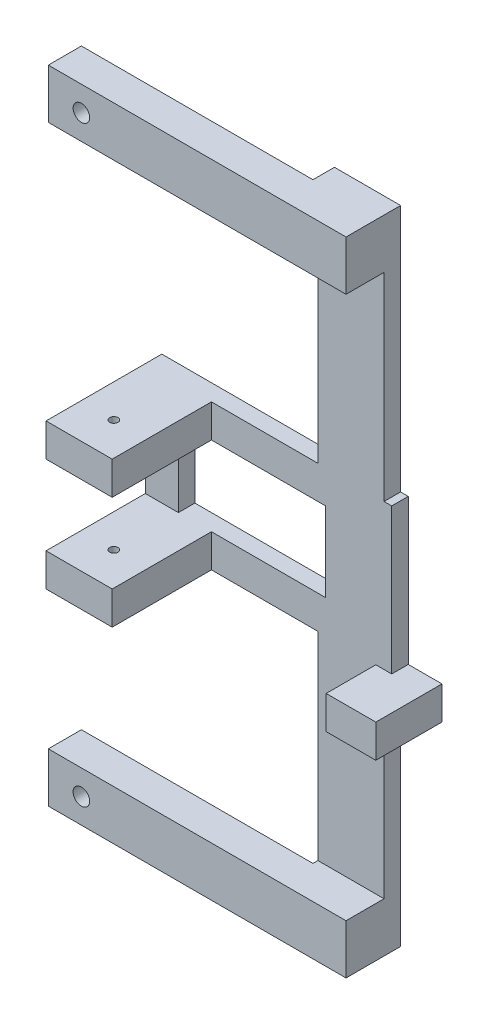
SolidWorks part; units mm, degrees
ref_plane "Front Plane" through (0, 0, 0) normal (0, 0, 1) x (1, 0, 0)
ref_plane "Top Plane" through (0, 0, 0) normal (0, 1, 0) x (1, 0, 0)
ref_plane "Right Plane" through (0, 0, 0) normal (1, 0, 0) x (0, 0, -1)
sketch "Sketch2" plane through (0, 0, 0) normal (0, 0, 1) x (1, 0, 0)
  line L0 (-5.9086, 0.2686) -> (16.6974, 0.2686)
  line L1 (16.6974, 0.2686) -> (16.6974, 12.4606)
  line L2 (16.6974, 12.4606) -> (-5.9086, 12.4606)
  line L3 (-5.9086, 12.4606) -> (-5.9086, 0.2686)
  line L4 (26.8574, 17.5406) -> (26.8574, -4.8114)
  line L6 (-10.9886, -4.8114) -> (-10.9886, 17.5406)
  line L13 (-10.9886, -4.8114) -> (15.521, -4.8114)
  line L16 (26.8574, 17.5406) -> (25.681, 17.5406)
  line L18 (15.521, 17.5406) -> (-10.9886, 17.5406)
  line L19 (15.521, -4.8114) -> (15.521, -42.9114)
  line L20 (15.521, -42.9114) -> (25.681, -42.9114)
  line L21 (25.681, -42.9114) -> (25.681, -4.8114)
  line L22 (25.681, 17.5406) -> (25.681, 55.6406)
  line L23 (25.681, 55.6406) -> (15.521, 55.6406)
  line L24 (15.521, 55.6406) -> (15.521, 17.5406)
  line L25 (25.681, -4.8114) -> (26.8574, -4.8114)
  dimension "D1" = 22.352
  dimension "D2" = 5.08
  dimension "D3" = 10.16
  dimension "D4" = 10.16
  dimension "D5" = 12.192
  dimension "D6" = 22.606
  dimension "D7" = 22.352
  dimension "D8" = 5.08
  dimension "D9" = 38.1
  dimension "D10" = 1.1764
extrude "Boss-Extrude2" add sketch "Sketch2" along normal blind 2.54
sketch "Sketch3" plane through (0, 0, 2.54) normal (0, 0, 1) x (1, 0, 0)
  line L0 (-10.9886, 17.5406) -> (-10.9886, -4.8114) construction
  line L1 (-0.8286, 0.2686) -> (-10.9886, 0.2686)
  line L2 (-0.8286, 0.2686) -> (-0.8286, -4.8114)
  line L3 (-0.8286, -4.8114) -> (-10.9886, -4.8114)
  line L4 (-10.9886, 0.2686) -> (-10.9886, -4.8114)
  line L5 (-10.9886, -4.8114) -> (15.521, -4.8114) construction
  dimension "D1" = 10.16
extrude "Boss-Extrude3" add sketch "Sketch3" along normal blind 15.24
sketch "Sketch5" plane through (0, 0, 2.54) normal (0, 0, 1) x (1, 0, 0)
  line L0 (25.681, -42.9114) -> (25.681, -4.8114) construction
  line L1 (15.521, -42.9114) -> (25.681, -42.9114)
  line L2 (15.521, -42.9114) -> (15.521, -35.2914)
  line L3 (15.521, -35.2914) -> (25.681, -35.2914)
  line L4 (25.681, -42.9114) -> (25.681, -35.2914)
  dimension "D1" = 7.62
extrude "Boss-Extrude4" add sketch "Sketch5" along normal blind 5.842
sketch "Sketch6" plane through (15.521, 0, 0) normal (-1, 0, 0) x (0, 0, 1)
  line L1 (8.382, -35.2914) -> (3.302, -35.2914)
  line L2 (8.382, -35.2914) -> (8.382, -42.9114)
  line L3 (8.382, -42.9114) -> (3.302, -42.9114)
  line L4 (3.302, -35.2914) -> (3.302, -42.9114)
  dimension "D1" = 5.08
  dimension "D2" = 7.62
extrude "Boss-Extrude5" add sketch "Sketch6" along normal blind 35.56
sketch "Sketch8" plane through (0, 0, 8.382) normal (0, 0, 1) x (1, 0, 0)
  line L0 (-20.039, -42.9114) -> (-20.039, -35.2914) construction
  line L2 (25.681, -35.2914) -> (-20.039, -35.2914) construction
  circle A0 centre (-14.959, -39.1014) radius 1.27
  dimension "D1" = 2.54
  dimension "D2" = 5.08
  dimension "D3" = 3.81
extrude "Cut-Extrude2" cut sketch "Sketch8" against normal up to surface (5.08 mm away) contours A0 up to face at (-2.259, -39.1014, 3.302)
ref_plane "Plane2" through (0, 6.3646, 0) normal (0, 1, 0) x (1, 0, 0)
mirror "Mirror6" about plane through (0, 6.3646, 0) normal (0, 1, 0) of "Cut-Extrude2", "Boss-Extrude4", "Boss-Extrude3", "Boss-Extrude5"
sketch "Sketch4" plane through (0, 17.5406, 0) normal (0, 1, 0) x (1, 0, 0)
  line L0 (15.521, -2.54) -> (-0.8286, -2.54) construction
  line L1 (-10.9886, -17.78) -> (-10.9886, 0) construction
  circle A0 centre (-5.9086, -12.446) radius 0.635
  dimension "D1" = 1.27
  dimension "D2" = 9.906
  dimension "D3" = 5.08
extrude "Cut-Extrude4" cut sketch "Sketch4" against normal up to surface (22.352 mm away)
sketch "Sketch16" plane through (25.681, 0, 0) normal (1, 0, 0) x (0, 0, -1)
  line L6 (0, -4.8114) -> (-10.16, -4.8114)
  line L7 (0, -4.8114) -> (0, -9.8914)
  line L8 (0, -9.8914) -> (-10.16, -9.8914)
  line L9 (-10.16, -4.8114) -> (-10.16, -9.8914)
  dimension "D1" = 5.08
  dimension "D2" = 10.16
extrude "Boss-Extrude8" add sketch "Sketch16" along normal blind 6.35
sketch "Sketch20" plane through (0, -9.8914, 0) normal (0, -1, 0) x (-1, 0, 0)
  line L0 (-32.031, -10.16) -> (-25.681, -10.16) construction
  line L1 (-32.031, -10.16) -> (-32.031, 0) construction
  circle A0 centre (-28.983, -5.588) radius 0.889
  dimension "D1" = 4.572
  dimension "D2" = 1.778
  dimension ".12" = 3.048
extrude "Cut-Extrude7" cut sketch "Sketch20" against normal blind 3.556
sketch "Sketch21" plane through (25.681, 0, 0) normal (-1, 0, 0) x (0, 0, 1)
  line L1 (2.54, -4.8114) -> (10.16, -4.8114)
  line L2 (2.54, -4.8114) -> (2.54, -9.8914)
  line L3 (2.54, -9.8914) -> (10.16, -9.8914)
  line L4 (10.16, -4.8114) -> (10.16, -9.8914)
extrude "Boss-Extrude9" add sketch "Sketch21" along normal blind 1.27
